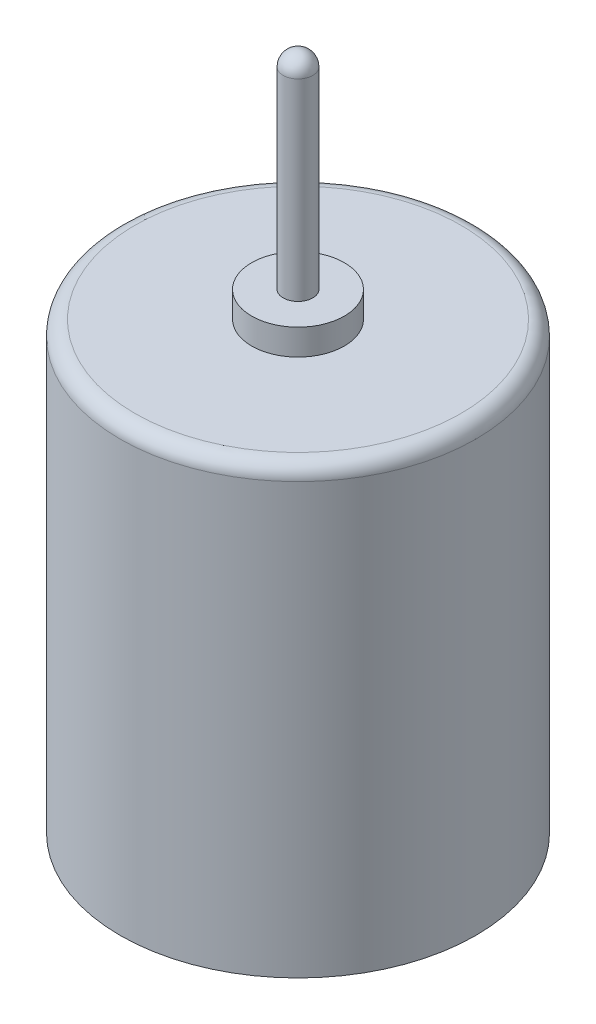
SolidWorks part; units mm, degrees
ref_plane "Front Plane" through (0, 0, 0) normal (0, 0, 1) x (1, 0, 0)
ref_plane "Top Plane" through (0, 0, 0) normal (0, 1, 0) x (1, 0, 0)
ref_plane "Right Plane" through (0, 0, 0) normal (1, 0, 0) x (0, 0, -1)
sketch "Sketch1" plane through (0, 0, 0) normal (0, 1, 0) x (1, 0, 0)
  circle A0 centre (0, 0) radius 12.192
  dimension "D1" = 24.384
extrude "Boss-Extrude1" add sketch "Sketch1" along normal blind 30.48
sketch "Sketch2" plane through (0, 30.48, 0) normal (0, 1, 0) x (1, 0, 0)
  circle A0 centre (0, 0) radius 3.175
  dimension "D1" = 6.35
extrude "Boss-Extrude2" add sketch "Sketch2" along normal blind 1.778
sketch "Sketch3" plane through (0, 32.258, 0) normal (0, 1, 0) x (1, 0, 0)
  circle A0 centre (0, 0) radius 1.016
  dimension "D1" = 2.032
extrude "Boss-Extrude3" add sketch "Sketch3" along normal blind 14.224
fillet "Fillet1" radius 1.016 1 edges at (0, 46.482, 1.016)
fillet "Fillet2" radius 1.016 1 edges at (0, 30.48, 12.192)
